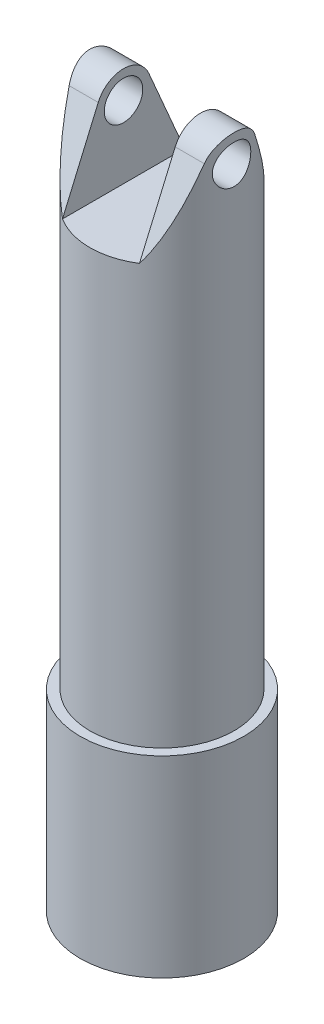
SolidWorks part; units mm, degrees
ref_plane "前视基准面" through (0, 0, 0) normal (0, 0, 1) x (1, 0, 0)
ref_plane "上视基准面" through (0, 0, 0) normal (0, 1, 0) x (1, 0, 0)
ref_plane "右视基准面" through (0, 0, 0) normal (1, 0, 0) x (0, 0, -1)
other "Configuration Table"
sketch "草图1" plane through (0, 0, 0) normal (0, 1, 0) x (1, 0, 0)
  circle A0 centre (0, 0) radius 17
extrude "凸台-拉伸1" add sketch "草图1" along normal blind 40
sketch "草图2" plane through (0, 40, 0) normal (0, 1, 0) x (1, 0, 0)
  circle A0 centre (0, 0) radius 15
extrude "凸台-拉伸2" add sketch "草图2" along normal blind 110
sketch "草图3" plane through (0, 0, 0) normal (0, 0, 1) x (1, 0, 0)
  line L0 (15, 150) -> (-15, 150) construction
  line L1 (-8, 173) -> (8, 173)
  line L2 (-8, 173) -> (-8, 127)
  line L3 (-8, 127) -> (8, 127)
  line L4 (8, 173) -> (8, 127)
  line L5 (0, 127) -> (0, 173) construction
  line L6 (-8, 150) -> (8, 150) construction
  point P0 (0, 150)
extrude "切除-拉伸1" cut sketch "草图3" against normal mid plane 30
sketch "草图4" plane through (0, 0, 0) normal (1, 0, 0) x (0, 0, -1)
  line L0 (0, 150) -> (0, 142) construction
  line L1 (12.6886, 150) -> (-12.6886, 150) construction
  circle A0 centre (0, 142) radius 4
extrude "切除-拉伸2" cut sketch "草图4" against normal mid plane 30 contours A0
sketch "草图5" plane through (0, 0, 0) normal (1, 0, 0) x (0, 0, -1)
  line L0 (0, 150) -> (0, 146) construction
  line L1 (12.6886, 150) -> (-12.6886, 150) construction
  line L10 (0, 146) -> (0, 142) construction
  circle A0 centre (0, 142) radius 4 construction
sketch "草图8" plane through (0, 0, 0) normal (1, 0, 0) x (0, 0, -1)
  line L0 (-12.6886, 127) -> (-5.2563, 144.263)
  line L1 (12.6886, 127) -> (5.2563, 144.263)
  line L2 (-12.6886, 127) -> (-12.6886, 150)
  line L3 (12.6886, 150) -> (-12.6886, 150) construction
  line L4 (-12.6886, 150) -> (-12.6886, 127) construction
  line L5 (-12.6886, 150) -> (12.6886, 150)
  line L6 (12.6886, 150) -> (12.6886, 127)
  arc A0 (5.2563, 144.263) -> (-5.2563, 144.263) centre (0, 142) ccw
extrude "切除-拉伸4" cut sketch "草图8" against normal mid plane 30
